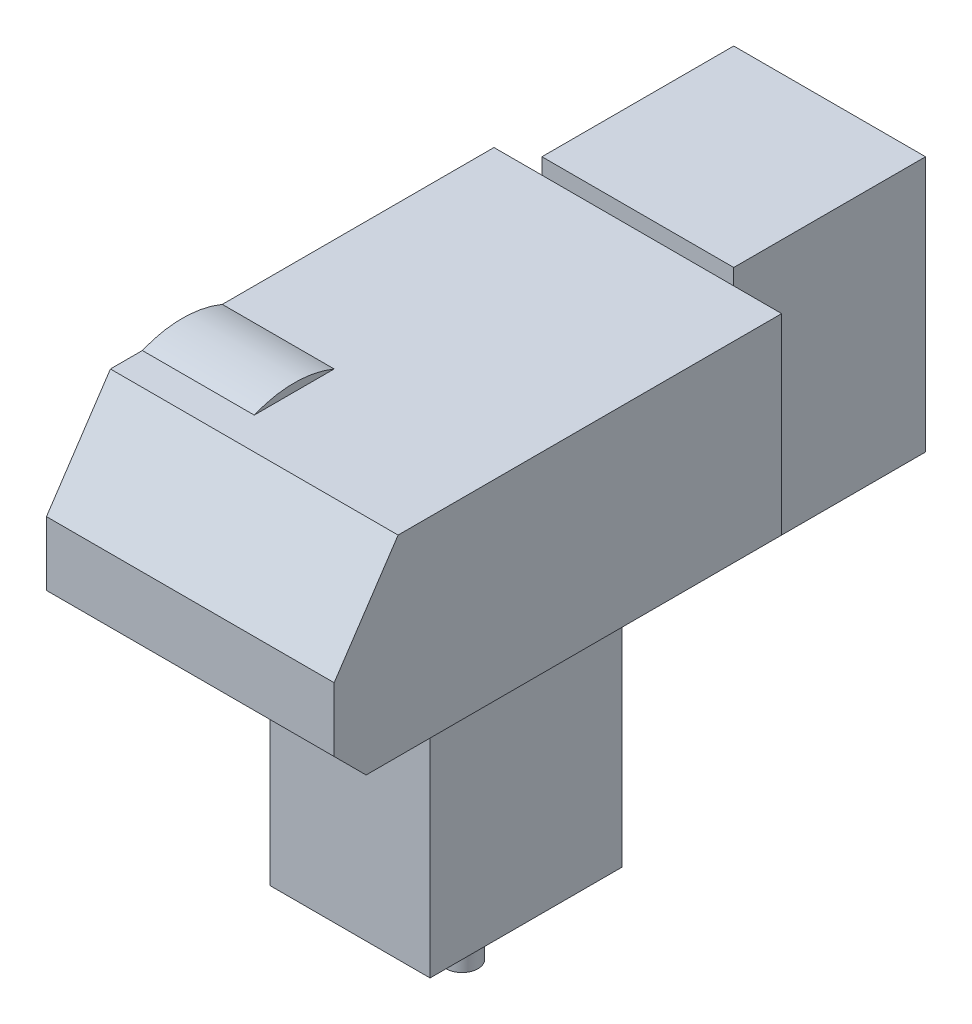
SolidWorks part; units mm, degrees
ref_plane "Front Plane" through (0, 0, 0) normal (0, 0, 1) x (1, 0, 0)
ref_plane "Top Plane" through (0, 0, 0) normal (0, 1, 0) x (1, 0, 0)
ref_plane "Right Plane" through (0, 0, 0) normal (1, 0, 0) x (0, 0, -1)
sketch "Sketch2" plane through (0, 0, 0) normal (0, 1, 0) x (1, 0, 0)
  line L1 (-63.5, -76.2) -> (63.5, -76.2)
  line L2 (-63.5, -76.2) -> (-63.5, 76.2)
  line L3 (-63.5, 76.2) -> (63.5, 76.2)
  line L4 (63.5, -76.2) -> (63.5, 76.2)
  line L5 (-63.5, -76.2) -> (63.5, 76.2) construction
  line L6 (-63.5, 76.2) -> (63.5, -76.2) construction
  point P0 (0, 0)
  dimension "D1" = 127
  dimension "D2" = 152.4
extrude "Boss-Extrude2" add sketch "Sketch2" along normal blind 215.9
sketch "Sketch3" plane through (0, 215.9, 0) normal (0, 1, 0) x (1, 0, 0)
  line L0 (63.5, 76.2) -> (-63.5, 76.2) construction
  line L5 (-114.3, -203.2) -> (114.3, -203.2)
  line L6 (-114.3, -203.2) -> (-114.3, 152.4)
  line L7 (-114.3, 152.4) -> (114.3, 152.4)
  line L8 (114.3, -203.2) -> (114.3, 152.4)
  line L9 (-114.3, -203.2) -> (114.3, 152.4) construction
  line L10 (-114.3, 152.4) -> (114.3, -203.2) construction
  point P0 (0, -25.4)
  point P6 (0, 0)
  dimension "D1" = 355.6
  dimension "D2" = 228.6
  dimension "D3" = 76.2
extrude "Boss-Extrude3" add sketch "Sketch3" along normal blind 152.4 contours L6 L7 L8 L5
sketch "Sketch4" plane through (-114.3, 0, 0) normal (-1, 0, 0) x (0, 0, 1)
  line L0 (-152.4, 368.3) -> (-152.4, 215.9) construction
  line L1 (203.2, 368.3) -> (203.2, 215.9) construction
  circle A0 centre (95.25, 292.1) radius 82.55
  point P2 (82.8908, 290.2997)
  point P5 (-152.4, 292.1)
  dimension "D1" = 165.1
  dimension "D2" = 25.4
extrude "Boss-Extrude4" add sketch "Sketch4" against normal blind 88.9
sketch "Sketch5" plane through (-114.3, 0, 0) normal (-1, 0, 0) x (0, 0, 1)
  line L0 (203.2, 368.3) -> (203.2, 215.9) construction
  line L1 (203.2, 292.1) -> (152.4, 368.3)
  line L2 (203.2, 292.1) -> (203.2, 241.3)
  line L3 (203.2, 241.3) -> (177.8, 215.9)
  line L5 (203.2, 215.9) -> (177.8, 215.9)
  line L6 (203.2, 368.3) -> (127, 368.3) construction
  line L7 (203.2, 215.9) -> (127, 215.9) construction
  line L8 (152.4, 368.3) -> (203.2, 368.3)
  line L9 (203.2, 368.3) -> (203.2, 292.1)
  line L10 (203.2, 241.3) -> (203.2, 215.9)
  line M5 (203.2, 368.3) -> (127, 368.3)
  line M11 (127, 215.9) -> (203.2, 215.9)
  line M12 (203.2, 215.9) -> (203.2, 368.3)
  dimension "D1" = 50.8
  dimension "D2" = 25.4
  dimension "D3" = 25.4
  dimension "D4" = 50.8
extrude "Cut-Extrude1" cut sketch "Sketch5" against normal through all contours L1 M12 M5 | L3 M12 M11
sketch "Sketch6" plane through (0, 0, -152.4) normal (0, 0, -1) x (-1, 0, 0)
  line L0 (63.5, 215.9) -> (114.3, 215.9) construction
  line L1 (76.2, 177.8) -> (-76.2, 177.8)
  line L2 (76.2, 177.8) -> (76.2, 381)
  line L3 (76.2, 381) -> (-76.2, 381)
  line L4 (-76.2, 177.8) -> (-76.2, 381)
  line L5 (76.2, 177.8) -> (-76.2, 381) construction
  line L6 (76.2, 381) -> (-76.2, 177.8) construction
  point P0 (0, 279.4)
  point P5 (0, 0)
  dimension "D1" = 203.2
  dimension "D2" = 152.4
  dimension "D3" = 38.1
extrude "Boss-Extrude5" add sketch "Sketch6" along normal blind 152.4
sketch "Sketch7" plane through (0, 0, 0) normal (0, -1, 0) x (1, 0, 0)
  line L0 (63.5, -76.2) -> (-63.5, -76.2) construction
  circle A0 centre (0, -12.7) radius 12.7
  point P4 (0, 0)
  dimension "D3" = 25.4
  dimension "D1" = 63.5
extrude "Boss-Extrude6" add sketch "Sketch7" along normal blind 63.5
